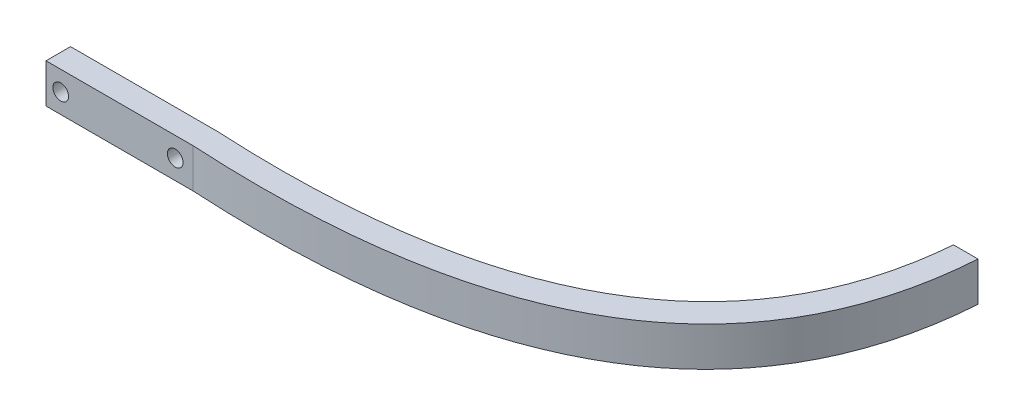
SolidWorks part; units mm, degrees
ref_plane "Спереди" through (0, 0, 0) normal (0, 0, 1) x (1, 0, 0)
ref_plane "Сверху" through (0, 0, 0) normal (0, 1, 0) x (1, 0, 0)
ref_plane "Справа" through (0, 0, 0) normal (1, 0, 0) x (0, 0, -1)
other "Configuration Table"
sketch "Эскиз1" plane through (0, 0, 0) normal (0, 1, 0) x (1, 0, 0)
  line L0 (120.6748, 57.761) -> (125.6748, 57.761)
  line L1 (-4.3252, 2.761) -> (25.6748, 2.761)
  line L2 (-4.3252, 2.761) -> (-4.3252, -2.239)
  line L3 (-4.3252, -2.239) -> (25.6748, -2.239)
  line L4 (25.6748, 2.761) -> (25.6748, -2.239)
  spline S0 degree 2 poles (25.6748, 2.761) (115.6932, -1.9858) (120.6748, 57.761) knots 0 0 0 1 1 1
  spline S1 degree 2 poles (25.6748, -2.239) (121.2876, -7.6434) (125.6748, 57.761) knots 0 0 0 1 1 1
  dimension "D1" = 30
  dimension "D2" = 5
  dimension "D3" = 5
  dimension "D4" = 130
  dimension "D5" = 55
extrude "Бобышка-Вытянуть1" add sketch "Эскиз1" along normal blind 8 contours L4 S1 L0 S0
sketch "Эскиз2" plane through (0, 0, -2.761) normal (0, 0, -1) x (-1, 0, 0)
  line L0 (4.3252, 8) -> (4.3252, 0) construction
  line L1 (4.3252, 8) -> (-25.6748, 8) construction
  circle A0 centre (-22.0148, 4) radius 1.6
  circle A1 centre (1.3252, 4) radius 1.6
  dimension "D2" = 3.2
  dimension "D1" = 23.34
  dimension "D3" = 3
  dimension "D4" = 4
  dimension "D5" = 4
extrude "Вырез-Вытянуть1" cut sketch "Эскиз2" against normal blind 10
